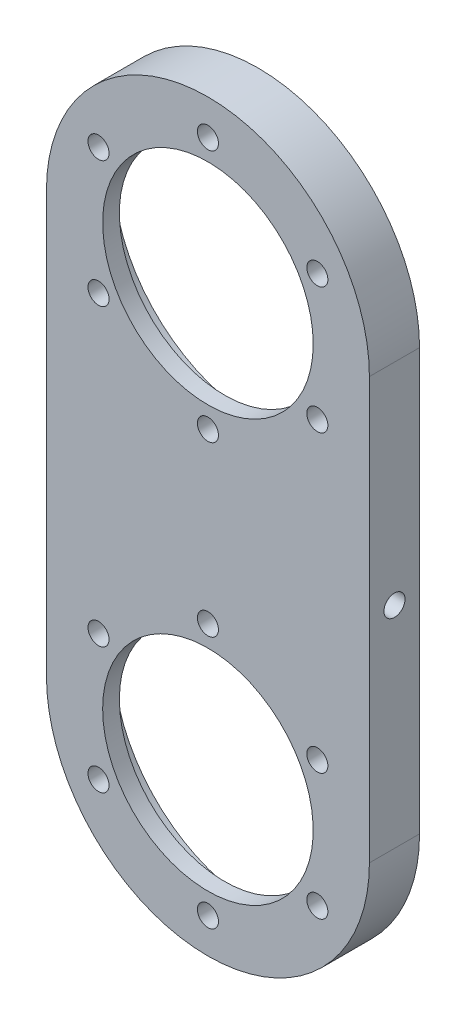
SolidWorks part; units mm, degrees
material "6061-T6 (SS)"
ref_plane "Front Plane" through (0, 0, 0) normal (0, 0, 1) x (1, 0, 0)
ref_plane "Top Plane" through (0, 0, 0) normal (0, 1, 0) x (1, 0, 0)
ref_plane "Right Plane" through (0, 0, 0) normal (1, 0, 0) x (0, 0, -1)
sketch "Sketch1" plane through (0, 0, 0) normal (0, 0, 1) x (1, 0, 0)
  line L0 (-30.675, 40) -> (-30.675, -40)
  line L1 (30.675, -40) -> (30.675, 40)
  line L2 (0, 62.8715) -> (0, -62.8715) construction
  line L3 (-30.675, 0) -> (30.675, 0) construction
  line L15 (-30.675, 40) -> (27.5, 40) construction
  line L16 (0, 62.8715) -> (0, 75) construction
  circle A2 centre (0, 40) radius 27.5
  circle A3 centre (0, -40) radius 27.5
  circle A4 centre (18.175, 0) radius 2.5 construction
  circle A5 centre (-18.175, 0) radius 2.5 construction
  arc A6 (30.675, 40) -> (-30.675, 40) centre (0, 40) ccw
  arc A7 (-30.675, -40) -> (30.675, -40) centre (0, -40) ccw
  point P8 (0, 0)
  point P18 (0, 65.6401)
  point P30 (0, -65.6401)
  dimension "D4" = 55
  dimension "D5" = 5
  dimension "D1" = 80
  dimension "D2" = 61.35
  dimension "D3" = 12.5
extrude "Boss-Extrude1" add sketch "Sketch1" along normal blind 9.525
sketch "Sketch2" plane through (0, 0, 9.525) normal (0, 0, 1) x (1, 0, 0)
  line L0 (-30.675, 0) -> (30.675, 0) construction
  line L1 (-27.5, 40) -> (27.5, 40) construction
  line L2 (-30.675, 40) -> (-30.675, -40)
  line L3 (30.675, -40) -> (30.675, 40)
  line L4 (-30.675, 40) -> (-30.675, -40)
  line L5 (30.675, -40) -> (30.675, 40)
  circle A0 centre (0, 40) radius 20
  circle A2 centre (0, 40) radius 27.5 construction
  circle A6 centre (0, 40) radius 24 construction
  circle A7 centre (0, 64) radius 2
  circle A8 centre (20.7846, 52) radius 2
  circle A9 centre (20.7846, 28) radius 2
  circle A10 centre (0, 16) radius 2
  circle A11 centre (-20.7846, 28) radius 2
  circle A12 centre (-20.7846, 52) radius 2
  circle A13 centre (0, -40) radius 24 construction
  circle A14 centre (-20.7846, -52) radius 2
  circle A15 centre (-20.7846, -28) radius 2
  circle A16 centre (0, -16) radius 2
  circle A17 centre (20.7846, -28) radius 2
  circle A18 centre (20.7846, -52) radius 2
  circle A19 centre (0, -64) radius 2
  circle A20 centre (0, -40) radius 20
  arc A22 (30.675, 40) -> (-30.675, 40) centre (0, 40) ccw
  arc A23 (30.675, 40) -> (-30.675, 40) centre (0, 40) ccw
  arc A24 (-30.675, -40) -> (30.675, -40) centre (0, -40) ccw
  arc A25 (-30.675, -40) -> (30.675, -40) centre (0, -40) ccw
  point P25 (0, 40)
  point P37 (0, -40)
  dimension "D2" = 40
  dimension "D3" = 48
  dimension "D4" = 4
  dimension "D1" = 0
  dimension "D5" = 6
extrude "Boss-Extrude2" add sketch "Sketch2" against normal blind 3.175
sketch "Sketch4" [suppressed] plane through (0, 63.5, 0) normal (0, 1, 0) x (1, 0, 0)
  line L0 (-13.175, -4.7625) -> (18.175, -4.7625) construction
  line L3 (0, 0.4369) -> (0, -9.525) construction
  line L4 (30.675, -9.525) -> (-30.675, -9.525) construction
  line L5 (-30.675, -9.525) -> (-30.675, 0) construction
  circle A0 centre (-20.675, -4.7625) radius 2.5
  circle A1 centre (20.675, -4.7625) radius 2.5
  dimension "D1" = 5
  dimension "D2" = 10
sketch "Sketch7" [suppressed] plane through (0, 0, 0) normal (0, 0, -1) x (-1, 0, 0)
  line L0 (-27.5, 32.2375) -> (-27.5, 12.6232)
  line L1 (-30.675, -12.6232) -> (-27.5, -12.6232)
  line L2 (27.5, -32.2375) -> (27.5, -12.6232)
  line L3 (30.675, -12.6232) -> (30.675, 12.6232)
  line L4 (30.675, 12.6232) -> (27.5, 12.6232)
  line L5 (-30.675, 12.6232) -> (-30.675, -12.6232)
  line L6 (-27.5, -12.6232) -> (-27.5, -32.2375)
  line L7 (-27.5, 12.6232) -> (-30.675, 12.6232)
  line L8 (27.5, 12.6232) -> (27.5, 32.2375)
  line L9 (27.5, -12.6232) -> (30.675, -12.6232)
  circle A0 centre (0, -32.2375) radius 27.5 construction
  circle A1 centre (0, 32.2375) radius 27.5 construction
  arc A2 (-27.5, -32.2375) -> (27.5, -32.2375) centre (0, -32.2375) ccw
  arc A3 (27.5, 32.2375) -> (-27.5, 32.2375) centre (0, 32.2375) ccw
extrude "Cut-Extrude4" [suppressed] cut sketch "Sketch7" against normal up to surface (6.35 mm away)
fillet "Fillet3" [suppressed] radius 5
extrude "Cut-Extrude5" [suppressed] cut sketch "Sketch4" against normal blind 10
mirror "Mirror1" [suppressed] about plane through (0, 0, 0) normal (0, 1, 0)
sketch "Sketch8" plane through (0, 0, 0) normal (1, 0, 0) x (0, 0, -1)
  line L0 (0, 0) -> (-9.525, 0) construction
  line L1 (-9.525, -40) -> (-9.525, 40) construction
  circle A0 centre (-4.7625, 0) radius 2
  dimension "D1" = 4
extrude "Cut-Extrude6" cut sketch "Sketch8" against normal mid plane 105
equation "\"d\"=5"
equation "\"D5@Sketch1\"=\"d\""
equation "\"D3@Sketch1\"=\"d\"*2.5"
